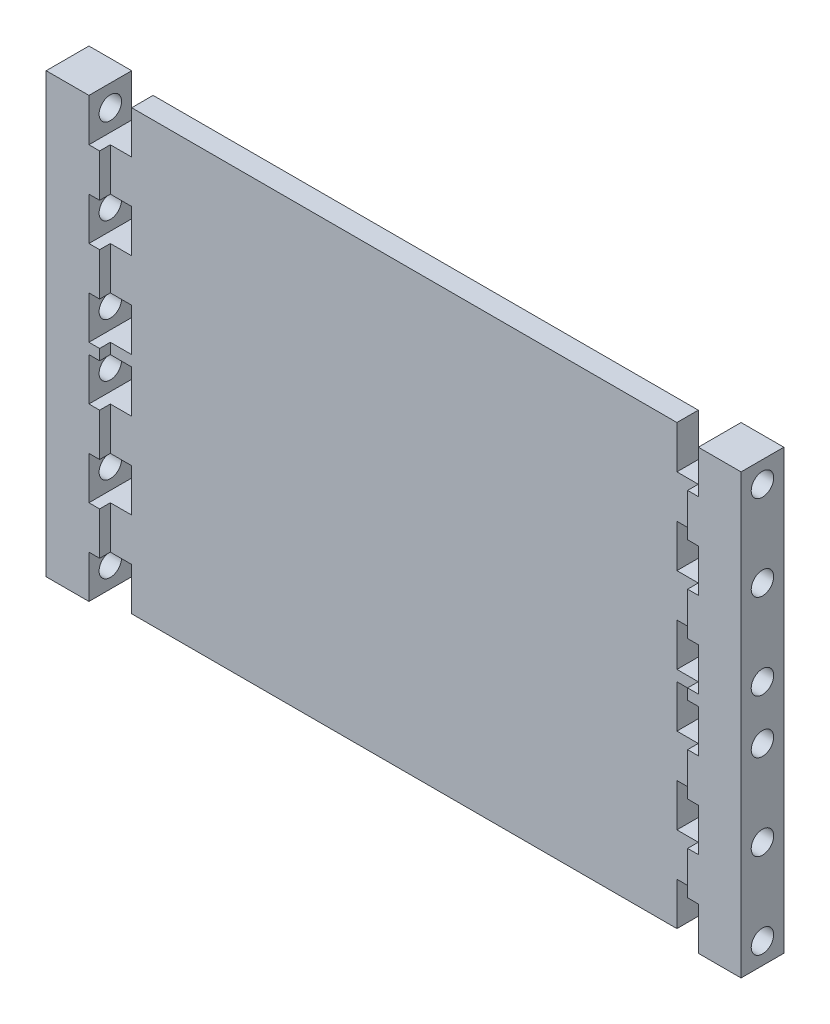
SolidWorks part; units mm, degrees
material "ABS"
ref_plane "前基準面" through (0, 0, 0) normal (0, 0, 1) x (1, 0, 0)
ref_plane "上基準面" through (0, 0, 0) normal (0, 1, 0) x (1, 0, 0)
ref_plane "右基準面" through (0, 0, 0) normal (1, 0, 0) x (0, 0, -1)
sketch "草圖1" plane through (0, 0, 0) normal (0, 0, 1) x (1, 0, 0)
  line L1 (-37.1398, 55.5253) -> (92.8602, 55.5253)
  line L2 (-37.1398, 55.5253) -> (-37.1398, -26.4747)
  line L3 (-37.1398, -26.4747) -> (92.8602, -26.4747)
  line L4 (92.8602, 55.5253) -> (92.8602, -26.4747)
  dimension "D1" = 130
  dimension "D2" = 82
extrude "填料-伸長1" add sketch "草圖1" along normal blind 8
sketch "草圖2" plane through (-37.1398, 0, 0) normal (-1, 0, 0) x (0, 0, 1)
  line L0 (8, 55.5253) -> (8, -26.4747) construction
  line L1 (8, -26.4747) -> (0, -26.4747) construction
  line L2 (8, 55.5253) -> (0, 55.5253) construction
  circle A0 centre (4, -22.4747) radius 2.1
  circle A1 centre (4, -6.4747) radius 2.1
  circle A2 centre (4, 9.5253) radius 2.1
  circle A3 centre (4, 19.5253) radius 2.1
  circle A4 centre (4, 35.5253) radius 2.1
  circle A5 centre (4, 51.5253) radius 2.1
  dimension "D1" = 4.2
  dimension "D2" = 4
  dimension "D3" = 4
  dimension "D6" = 4
  dimension "D4" = 3
  dimension "D5" = 2
extrude "除料-伸長1" cut sketch "草圖2" against normal through all
sketch "草圖3" plane through (0, 0, 0) normal (0, 0, -1) x (-1, 0, 0)
  line L0 (-92.8602, 55.5253) -> (37.1398, 55.5253) construction
  line L1 (-82.8602, 55.5253) -> (27.1398, 55.5253)
  line L2 (-82.8602, 55.5253) -> (-82.8602, -26.4747)
  line L3 (-82.8602, -26.4747) -> (27.1398, -26.4747)
  line L4 (27.1398, 55.5253) -> (27.1398, -26.4747)
  line L5 (37.1398, -26.4747) -> (-92.8602, -26.4747) construction
  line L6 (37.1398, 55.5253) -> (37.1398, -26.4747) construction
  line L7 (-92.8602, -26.4747) -> (-92.8602, 55.5253) construction
  dimension "D1" = 10
  dimension "D2" = 10
extrude "填料-伸長2" add sketch "草圖3" against normal blind 8
sketch "草圖4" plane through (0, -26.4747, 0) normal (0, -1, 0) x (1, 0, 0)
  line L0 (-37.1398, 8) -> (92.8602, 8) construction
  line L1 (-27.1398, 8) -> (82.8602, 8)
  line L2 (-27.1398, 8) -> (-27.1398, 6)
  line L3 (-27.1398, 6) -> (82.8602, 6)
  line L4 (82.8602, 8) -> (82.8602, 6)
  line L5 (-37.1398, 0) -> (92.8602, 0) construction
  line L6 (-27.1398, 0) -> (82.8602, 0)
  line L7 (-27.1398, 0) -> (-27.1398, 2)
  line L8 (-27.1398, 2) -> (82.8602, 2)
  line L9 (82.8602, 0) -> (82.8602, 2)
  line L10 (92.8602, 8) -> (92.8602, 0) construction
  line L11 (-37.1398, 8) -> (-37.1398, 0) construction
  dimension "D1" = 10
  dimension "D2" = 10
  dimension "D3" = 10
  dimension "D4" = 10
  dimension "D5" = 2
  dimension "D6" = 2
extrude "除料-伸長2" cut sketch "草圖4" against normal through all
sketch "草圖7" plane through (0, 0, 8) normal (0, 0, 1) x (1, 0, 0)
  line L0 (-27.1398, 55.5253) -> (-37.1398, 55.5253) construction
  line L1 (-29.1398, 55.5253) -> (-23.1398, 55.5253)
  line L2 (-29.1398, 55.5253) -> (-29.1398, 47.5253)
  line L3 (-29.1398, 47.5253) -> (-23.1398, 47.5253)
  line L4 (-23.1398, 55.5253) -> (-23.1398, 47.5253)
  line L5 (-27.1398, 55.5253) -> (-27.1398, -26.4747) construction
  line L6 (92.8602, 55.5253) -> (82.8602, 55.5253) construction
  line L7 (84.8602, 55.5253) -> (78.8602, 55.5253)
  line L8 (84.8602, 55.5253) -> (84.8602, 47.5253)
  line L9 (84.8602, 47.5253) -> (78.8602, 47.5253)
  line L10 (78.8602, 55.5253) -> (78.8602, 47.5253)
  line L11 (82.8602, 55.5253) -> (82.8602, -26.4747) construction
  line L12 (-29.1398, 39.5253) -> (-23.1398, 39.5253)
  line L13 (-23.1398, 39.5253) -> (-23.1398, 31.5253)
  line L14 (-29.1398, 31.5253) -> (-23.1398, 31.5253)
  line L15 (-29.1398, 39.5253) -> (-29.1398, 31.5253)
  line L16 (84.8602, 39.5253) -> (84.8602, 31.5253)
  line L17 (84.8602, 39.5253) -> (78.8602, 39.5253)
  line L18 (78.8602, 39.5253) -> (78.8602, 31.5253)
  line L19 (84.8602, 31.5253) -> (78.8602, 31.5253)
  line L20 (-29.1398, 23.5253) -> (-23.1398, 23.5253)
  line L21 (-23.1398, 23.5253) -> (-23.1398, 15.5253)
  line L22 (-29.1398, 15.5253) -> (-23.1398, 15.5253)
  line L23 (-29.1398, 23.5253) -> (-29.1398, 15.5253)
  line L24 (84.8602, 23.5253) -> (84.8602, 15.5253)
  line L25 (84.8602, 23.5253) -> (78.8602, 23.5253)
  line L26 (78.8602, 23.5253) -> (78.8602, 15.5253)
  line L27 (84.8602, 15.5253) -> (78.8602, 15.5253)
  line L28 (-29.1398, 13.5253) -> (-23.1398, 13.5253)
  line L29 (-29.1398, 13.5253) -> (-29.1398, 5.5253)
  line L30 (-29.1398, 5.5253) -> (-23.1398, 5.5253)
  line L31 (-23.1398, 13.5253) -> (-23.1398, 5.5253)
  line L32 (84.8602, 13.5253) -> (78.8602, 13.5253)
  line L33 (84.8602, 13.5253) -> (84.8602, 5.5253)
  line L34 (84.8602, 5.5253) -> (78.8602, 5.5253)
  line L35 (78.8602, 13.5253) -> (78.8602, 5.5253)
  line L36 (-29.1398, -2.4747) -> (-23.1398, -2.4747)
  line L37 (-23.1398, -2.4747) -> (-23.1398, -10.4747)
  line L38 (-29.1398, -10.4747) -> (-23.1398, -10.4747)
  line L39 (-29.1398, -2.4747) -> (-29.1398, -10.4747)
  line L40 (84.8602, -2.4747) -> (84.8602, -10.4747)
  line L41 (84.8602, -2.4747) -> (78.8602, -2.4747)
  line L42 (78.8602, -2.4747) -> (78.8602, -10.4747)
  line L43 (84.8602, -10.4747) -> (78.8602, -10.4747)
  line L44 (-29.1398, -18.4747) -> (-23.1398, -18.4747)
  line L45 (-23.1398, -18.4747) -> (-23.1398, -26.4747)
  line L46 (-29.1398, -26.4747) -> (-23.1398, -26.4747)
  line L47 (-29.1398, -18.4747) -> (-29.1398, -26.4747)
  line L48 (84.8602, -18.4747) -> (84.8602, -26.4747)
  line L49 (84.8602, -18.4747) -> (78.8602, -18.4747)
  line L50 (78.8602, -18.4747) -> (78.8602, -26.4747)
  line L51 (84.8602, -26.4747) -> (78.8602, -26.4747)
  dimension "D1" = 8
  dimension "D2" = 6
  dimension "D3" = 2
  dimension "D4" = 6
  dimension "D5" = 2
  dimension "D6" = 8
  dimension "D7" = 3
  dimension "D8" = 2
extrude "除料-伸長3" cut sketch "草圖7" against normal blind 10
